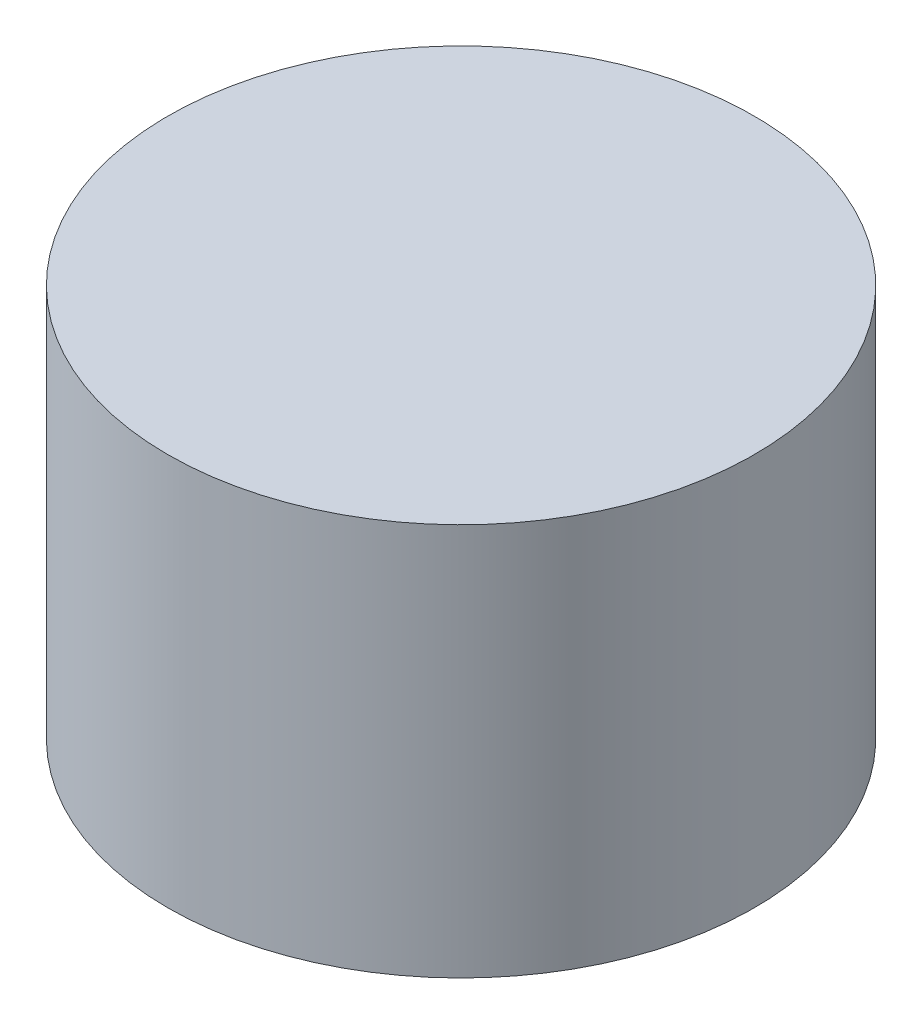
SolidWorks part; units mm, degrees
ref_plane "Front Plane" through (0, 0, 0) normal (0, 0, 1) x (1, 0, 0)
ref_plane "Top Plane" through (0, 0, 0) normal (0, 1, 0) x (1, 0, 0)
ref_plane "Right Plane" through (0, 0, 0) normal (1, 0, 0) x (0, 0, -1)
sketch "Sketch1" plane through (0, 0, 0) normal (0, 1, 0) x (1, 0, 0)
  circle A0 centre (0, 0) radius 3.175
  dimension "D1" = 6.35
extrude "Boss-Extrude1" add sketch "Sketch1" along normal blind 4.25
